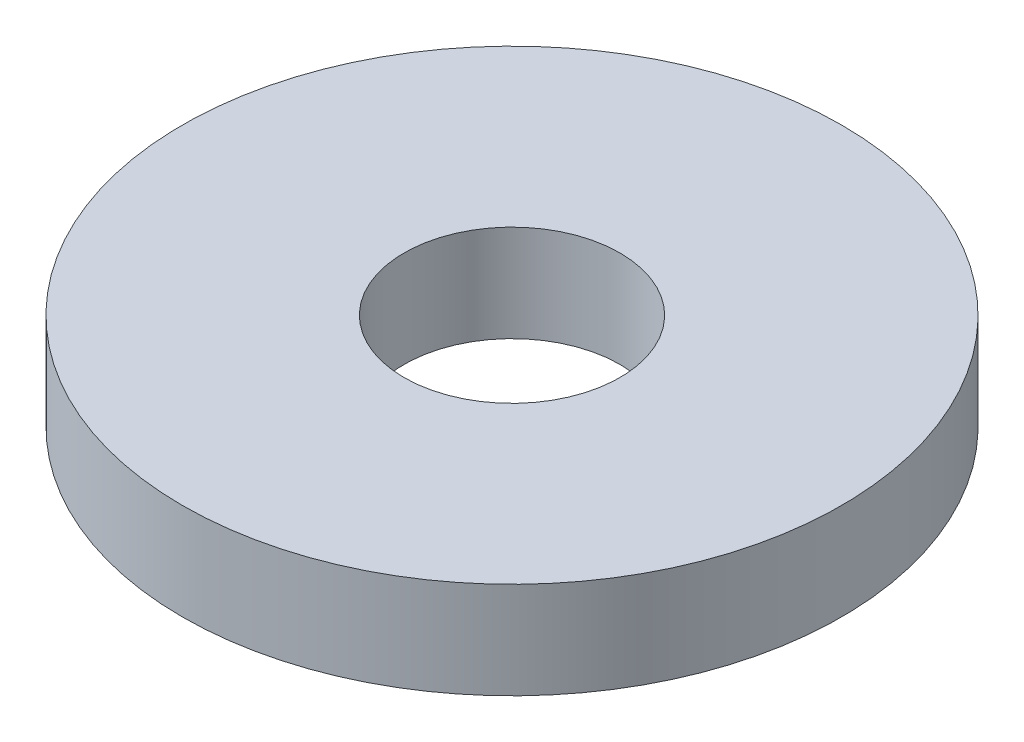
SolidWorks part; units mm, degrees
ref_plane "Front Plane" through (0, 0, 0) normal (0, 0, 1) x (1, 0, 0)
ref_plane "Top Plane" through (0, 0, 0) normal (0, 1, 0) x (1, 0, 0)
ref_plane "Right Plane" through (0, 0, 0) normal (1, 0, 0) x (0, 0, -1)
sketch "Sketch1" plane through (0, 0, 0) normal (0, 1, 0) x (1, 0, 0)
  circle A0 centre (0, 0) radius 10.3124
  dimension "OD" = 20.6248
extrude "Boss-Extrude1" add sketch "Sketch1" along normal blind 3.0226
sketch "Sketch5" plane through (0, 3.0226, 0) normal (0, 1, 0) x (-1, 0, 0)
  circle A0 centre (0, 0) radius 3.3782
  dimension "ID" = 6.7564
extrude "Cut-Extrude1" cut sketch "Sketch5" against normal through all
